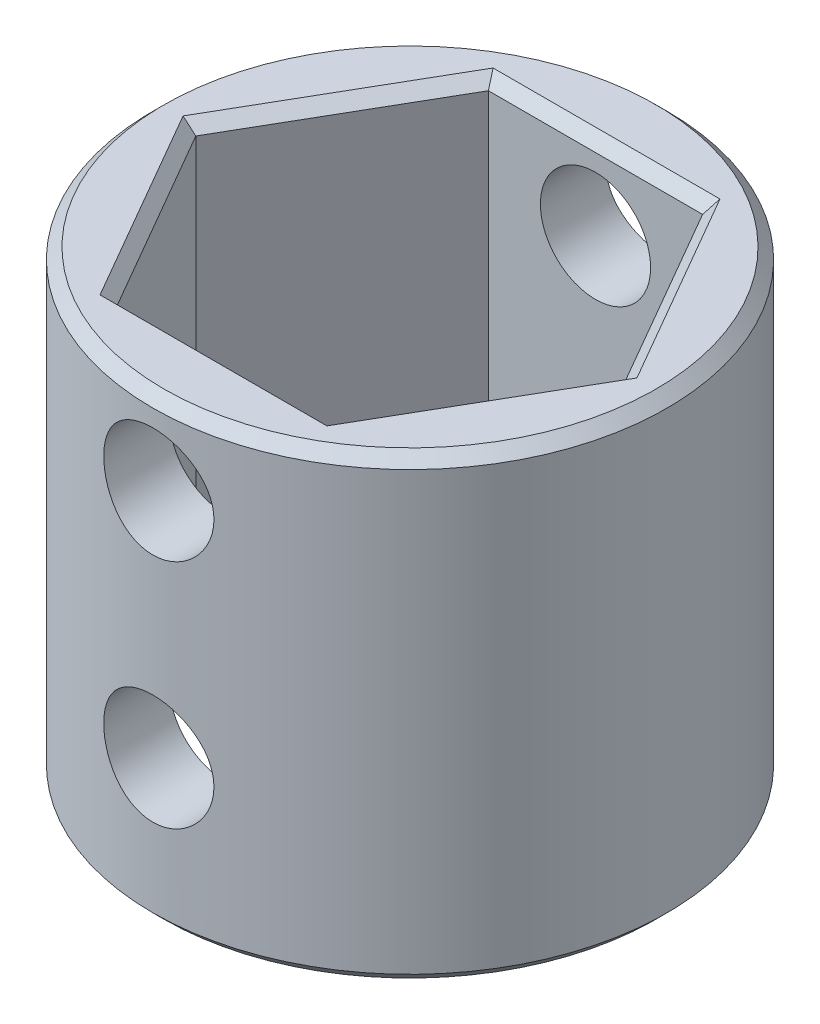
SolidWorks part; units mm, degrees
material "Markforged"
ref_plane "Front Plane" through (0, 0, 0) normal (0, 0, 1) x (1, 0, 0)
ref_plane "Top Plane" through (0, 0, 0) normal (0, 1, 0) x (1, 0, 0)
ref_plane "Right Plane" through (0, 0, 0) normal (1, 0, 0) x (0, 0, -1)
other "Bounding Box"
ref_plane "Default Plane" through (-8.9266, -12.7485, 0) normal (-0.1736, 0.9848, 0) x (0.9848, 0.1736, 0)
sketch "Sketch1" plane through (0, 0, 0) normal (0, 1, 0) x (1, 0, 0)
  line L1 (3.7028, -6.4135) -> (7.4057, 0)
  line L2 (7.4057, 0) -> (3.7028, 6.4135)
  line L3 (3.7028, 6.4135) -> (-3.7028, 6.4135)
  line L4 (-3.7028, 6.4135) -> (-7.4057, 0)
  line L5 (-7.4057, 0) -> (-3.7028, -6.4135)
  line L6 (-3.7028, -6.4135) -> (3.7028, -6.4135)
  circle A0 centre (0, 0) radius 6.4135 construction
  circle A1 centre (0, 0) radius 8.89
  dimension "D2" = 17.78
  dimension "D1" = 12.827
extrude "Boss-Extrude1" add sketch "Sketch1" along normal mid plane 15.875
sketch "Sketch3" plane through (0, 0, 0) normal (0, 0, 1) x (1, 0, 0)
  line L0 (-8.89, -7.9375) -> (8.89, -7.9375) construction
  circle A0 centre (0, -2.9375) radius 1.905
  circle A1 centre (0, 5.0625) radius 1.905
  point P6 (0, 0)
  point P8 (0, 0)
  dimension "D3" = 3.81
  dimension "D1" = 5
  dimension "D2" = 8
chamfer "Chamfer1" distance 0.381 angle 45 14 edges at (0, -7.9375, 8.89) (0, 7.9375, 8.89) (-5.5543, -7.9375, 3.2067) (-5.5543, -7.9375, -3.2068) (0, -7.9375, -6.4135) (5.5543, -7.9375, -3.2068) (5.5543, -7.9375, 3.2067) (0, -7.9375, 6.4135) (5.5543, 7.9375, -3.2068) (0, 7.9375, -6.4135) (-5.5543, 7.9375, -3.2068) (-5.5543, 7.9375, 3.2067) (0, 7.9375, 6.4135) (5.5543, 7.9375, 3.2067)
extrude "Cut-Extrude1" cut sketch "Sketch3" against normal through all and the other way through all
